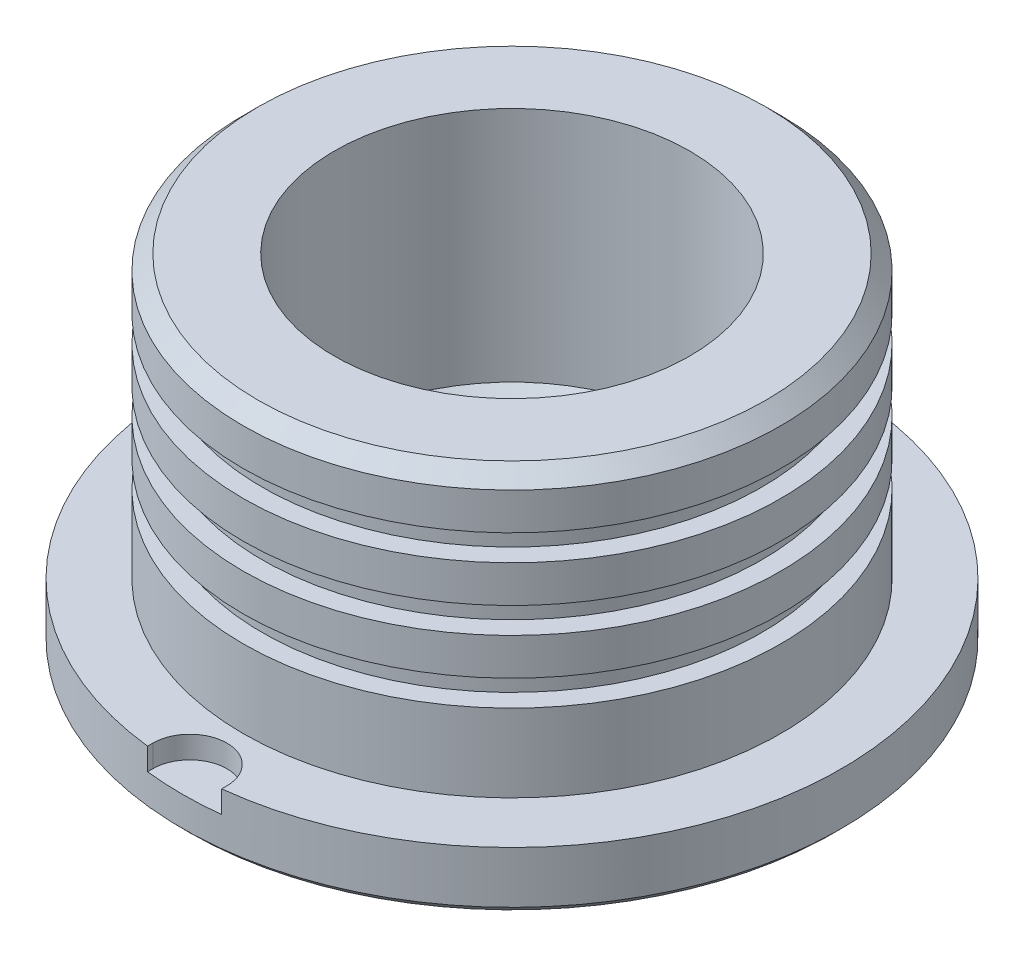
SolidWorks part; units mm, degrees
ref_plane "Plano frontal" through (0, 0, 0) normal (0, 0, 1) x (1, 0, 0)
ref_plane "Plano superior" through (0, 0, 0) normal (0, 1, 0) x (1, 0, 0)
ref_plane "Plano direito" through (0, 0, 0) normal (1, 0, 0) x (0, 0, -1)
sketch "Esboço1" plane through (0, 0, 0) normal (0, 0, 1) x (1, 0, 0)
  line L19 (0, 0) -> (0, 111187.7924) construction
  line L34 (44.5, 0) -> (44.5, 8)
  line L35 (44.5, 8) -> (36.3, 8)
  line L41 (36.3, 18.5) -> (33.7, 18.5)
  line L42 (33.7, 18.5) -> (33.7, 22)
  line L43 (33.7, 22) -> (36.3, 22)
  line L44 (36.3, 22) -> (36.3, 27)
  line L45 (36.3, 27) -> (33.7, 27)
  line L46 (33.7, 27) -> (33.7, 30.5)
  line L47 (33.7, 30.5) -> (36.3, 30.5)
  line L48 (36.3, 30.5) -> (36.3, 35.5)
  line L49 (36.3, 35.5) -> (33.7, 35.5)
  line L50 (33.7, 35.5) -> (33.7, 39)
  line L51 (33.7, 39) -> (36.3, 39)
  line L52 (36.3, 39) -> (36.3, 46)
  line L53 (36.3, 46) -> (24, 46)
  line L55 (24, 46) -> (24, 12)
  line L83 (24, 12) -> (0, 12)
  line L84 (0, 12) -> (0, 0)
  line L85 (0, 0) -> (44.5, 0)
  line L86 (36.3, 18.5) -> (36.3, 8)
  point P49 (0, 0)
  dimension "D1" = 8
  dimension "D2" = 10.5
  dimension "D4" = 3.5
  dimension "D5" = 7
  dimension "D6" = 89
  dimension "D7" = 72.6
  dimension "D8" = 67.4
  dimension "D9" = 5
  dimension "D10" = 12
  dimension "D11" = 48
revolve "Revolução1" add sketch "Esboço1" angle 360 about L19
sketch "Esboço2" plane through (0, 8, 0) normal (0, 1, 0) x (1, 0, 0)
  line L0 (0, 44.5) -> (0, -44.5) construction
  line L4 (0, 0) -> (44.5, 0) construction
  line L8 (0, 43.5) -> (0, 45.5) construction
  line L9 (-5, 43.5) -> (-5, 45.5)
  line L10 (5, 43.5) -> (5, 45.5)
  line L11 (0, -43.5) -> (0, -45.5) construction
  line L12 (-5, -43.5) -> (-5, -45.5)
  line L13 (5, -43.5) -> (5, -45.5)
  arc A0 (-5, 43.5) -> (5, 43.5) centre (0, 43.5) ccw
  circle A3 centre (0, 0) radius 44.5 construction
  arc A4 (5, 45.5) -> (-5, 45.5) centre (0, 45.5) ccw
  arc A5 (-5, -43.5) -> (5, -43.5) centre (0, -43.5) cw
  arc A6 (5, -45.5) -> (-5, -45.5) centre (0, -45.5) cw
  point P3 (0, 44.5)
  point P13 (0, -44.5)
  dimension "D1" = 5
  dimension "D2" = 6
extrude "Corte-extrusão1" cut sketch "Esboço2" against normal blind 3
sketch "Esboço4" plane through (0, 12, 0) normal (0, 1, 0) x (1, 0, 0)
  line L0 (-24, 0) -> (24, 0) construction
  line L1 (0, 24) -> (0, -24) construction
  line L2 (-9.9411, 9.9411) -> (-4.9411, 9.9411) construction
  line L3 (9.9411, 9.9411) -> (14.9411, 9.9411) construction
  line L4 (-9.9411, -9.9411) -> (-4.9411, -9.9411) construction
  line L5 (9.9411, -9.9411) -> (14.9411, -9.9411) construction
  circle A1 centre (-9.9411, 9.9411) radius 9.9411 construction
  circle A2 centre (-9.9411, 9.9411) radius 5
  circle A3 centre (9.9411, 9.9411) radius 5
  circle A4 centre (9.9411, -9.9411) radius 5
  circle A5 centre (-9.9411, -9.9411) radius 5
  circle A8 centre (0, 0) radius 24 construction
  circle A9 centre (0, 0) radius 24
  dimension "D2" = 10
extrude "Corte-extrusão2" cut sketch "Esboço4" against normal through all contours A2 | A3 | A5 | A4
cosmetic thread "Representação de rosca1" parameters "D2"=12
cosmetic thread "Representação de rosca2" parameters "D2"=12
cosmetic thread "Representação de rosca3" parameters "D2"=12
cosmetic thread "Representação de rosca4" parameters "D2"=12
chamfer "Chanfro1" distance 2 angle 45 1 edges at (0, 46, -36.3)
chamfer "Chanfro2" distance 2 angle 45 1 edges at (0, 12, -24)
chamfer "Chanfro3" distance 1 angle 45 1 edges at (0, 0, -44.5)
